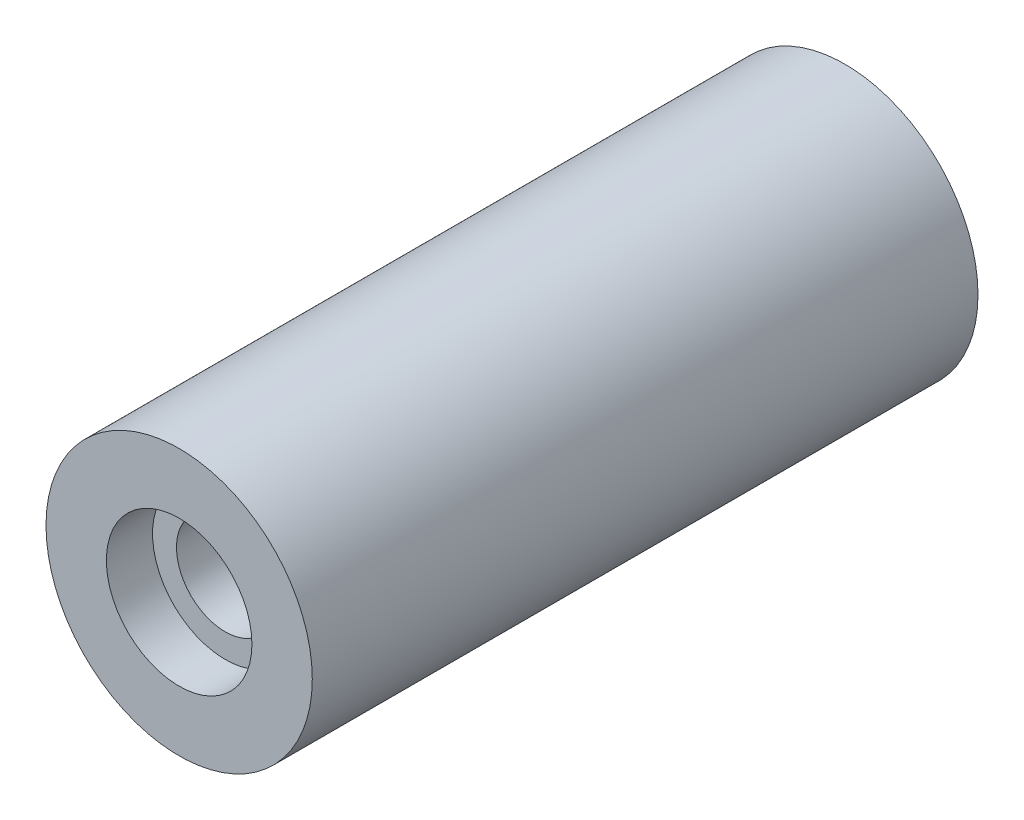
SolidWorks part; units mm, degrees
ref_plane "Front Plane" through (0, 0, 0) normal (0, 0, 1) x (1, 0, 0)
ref_plane "Top Plane" through (0, 0, 0) normal (0, 1, 0) x (1, 0, 0)
ref_plane "Right Plane" through (0, 0, 0) normal (1, 0, 0) x (0, 0, -1)
sketch "Sketch1" plane through (0, 0, 0) normal (0, 0, 1) x (1, 0, 0)
  circle A0 centre (0, 0) radius 15
  dimension "D1" = 30
extrude "Boss-Extrude1" add sketch "Sketch1" along normal blind 75
sketch "Sketch2" plane through (0, 0, 75) normal (0, 0, 1) x (1, 0, 0)
  circle A0 centre (0, 0) radius 8.2
  dimension "D1" = 16.4
extrude "Cut-Extrude1" cut sketch "Sketch2" against normal blind 5.2
sketch "Sketch3" plane through (0, 0, 0) normal (0, 0, -1) x (-1, 0, 0)
  circle A0 centre (0, 0) radius 8.2
  dimension "D1" = 16.4
extrude "Cut-Extrude2" cut sketch "Sketch3" against normal blind 5.2
sketch "Sketch4" plane through (0, 0, 69.8) normal (0, 0, 1) x (1, 0, 0)
  circle A0 centre (0, 0) radius 5.5
  dimension "D1" = 11
extrude "Cut-Extrude3" cut sketch "Sketch4" against normal blind 25
sketch "Sketch5" plane through (0, 0, 5.2) normal (0, 0, -1) x (-1, 0, 0)
  circle A0 centre (0, 0) radius 5.5
  dimension "D1" = 11
extrude "Cut-Extrude4" cut sketch "Sketch5" against normal blind 25
